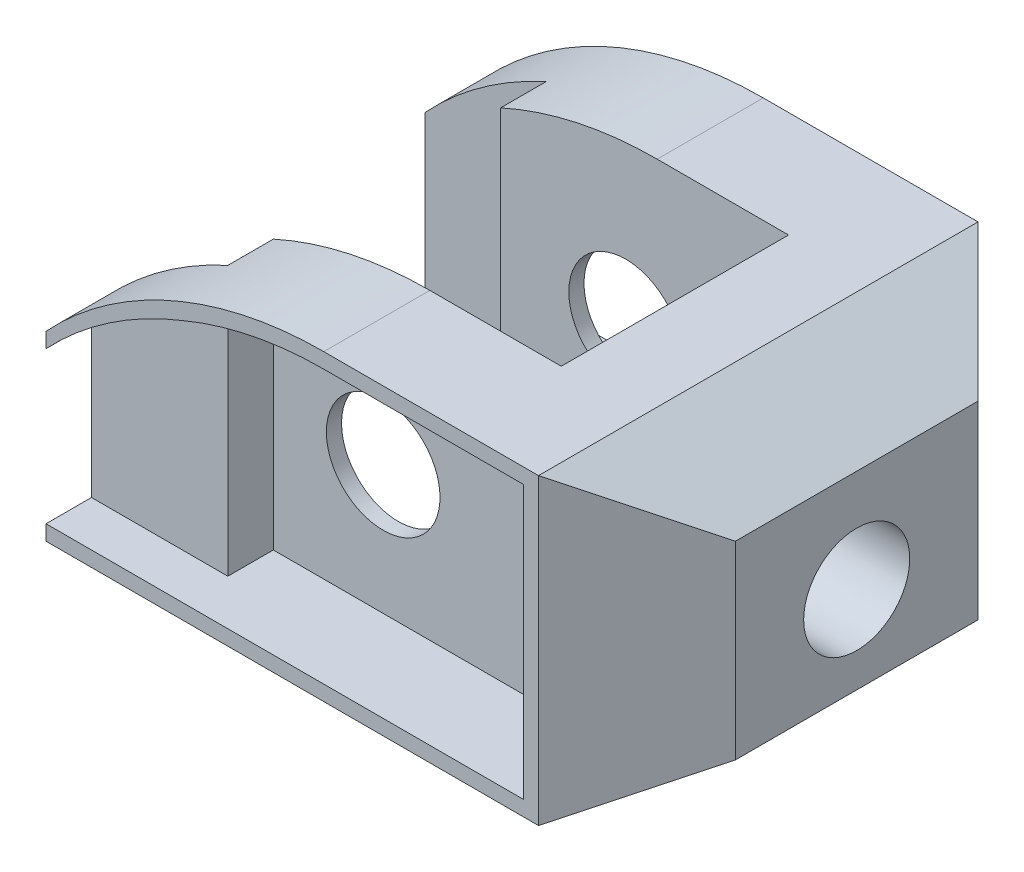
SolidWorks part; units mm, degrees
material "1060 Alloy"
ref_plane "Front Plane" through (0, 0, 0) normal (0, 0, 1) x (1, 0, 0)
ref_plane "Top Plane" through (0, 0, 0) normal (0, 1, 0) x (1, 0, 0)
ref_plane "Right Plane" through (0, 0, 0) normal (1, 0, 0) x (0, 0, -1)
sketch "Sketch1" plane through (0, 0, 0) normal (0, 0, 1) x (1, 0, 0)
  line L0 (0, 13.8138) -> (0, -28.7241) construction
  line L1 (32.5, -19) -> (-32.5, -19)
  line L2 (-32.5, -19) -> (-32.5, 5)
  line L3 (32.5, -19) -> (45.4904, -11.5)
  line L4 (45.4904, -11.5) -> (45.4904, 13.5)
  line L5 (45.4904, 13.5) -> (32.5, 21)
  line L6 (32.5, 21) -> (4.1606, 21)
  circle A0 centre (0, 0) radius 7.5
  arc A1 (-32.5, 5) -> (4.1606, 21) centre (4.1606, -29) cw
  point P8 (0, -19)
  dimension "D1" = 15
  dimension "D9" = 50
  dimension "D2" = 65
  dimension "D3" = 19
  dimension "D4" = 24
  dimension "D5" = 15
  dimension "D6" = 30
  dimension "D7" = 30
  dimension "D8" = 40
extrude "Boss-Extrude1" add sketch "Sketch1" along normal blind 58
sketch "Sketch2" plane through (0, 21, 0) normal (0, 1, 0) x (1, 0, 0)
  line L0 (45.4904, -29) -> (21.5, -29) construction
  line L1 (45.4904, -58) -> (45.4904, 0) construction
  line L2 (-32.5, -58) -> (-32.5, 0) construction
  line L3 (4.1606, -58) -> (4.1606, 0) construction
  line L4 (21.5, -44) -> (-16.5, -44)
  line L5 (21.5, -44) -> (21.5, -14)
  line L6 (21.5, -14) -> (-16.5, -14)
  line L7 (-16.5, -44) -> (-16.5, -14)
  line L8 (-16.5, -29) -> (-32.5, -29) construction
  line L9 (32.5, 0) -> (4.1606, 0) construction
  line L10 (32.5, -58) -> (32.5, 0) construction
  line L11 (32.5, -58) -> (4.1606, -58) construction
  point P6 (4.1606, -29)
  dimension "D1" = 11
  dimension "D2" = 16
  dimension "D3" = 14
  dimension "D4" = 14
extrude "Cut-Extrude1" cut sketch "Sketch2" against normal through all both and the other way through all
sketch "Sketch3" plane through (0, 21, 0) normal (0, 1, 0) x (1, 0, 0)
  line L0 (-32.5, -29) -> (45.4904, -29) construction
  line L1 (-32.5, -58) -> (-32.5, 0) construction
  line L2 (45.4904, -58) -> (45.4904, 0) construction
  line L3 (-16.5, -50) -> (-32.5, -50)
  line L4 (-16.5, -14) -> (-32.5, -14)
  line L5 (-16.5, -14) -> (-16.5, -8)
  line L6 (-16.5, -8) -> (-32.5, -8)
  line L7 (-32.5, -14) -> (-32.5, -8)
  line L8 (-32.5, -44) -> (-32.5, -50)
  line L9 (-16.5, -44) -> (-32.5, -44)
  line L10 (-16.5, -44) -> (-16.5, -50)
  dimension "D1" = 6
extrude "Cut-Extrude4" cut sketch "Sketch3" against normal through all both and the other way through all
sketch "Sketch4" plane through (45.4904, 0, 0) normal (1, 0, 0) x (0, 0, -1)
  line L0 (-58, -19) -> (0, -19) construction
  line L1 (-58, -11.5) -> (-58, 13.5) construction
  circle A0 centre (-29, 0) radius 7
  dimension "D1" = 14
  dimension "D2" = 19
  dimension "D3" = 29
extrude "Cut-Extrude5" cut sketch "Sketch4" against normal through all both and the other way through all
sketch "Sketch6" plane through (0, 21, 0) normal (0, 1, 0) x (1, 0, 0)
  line L0 (32.5, 0) -> (45.4904, -12.9904)
  line L1 (45.4904, -58) -> (45.4904, 0) construction
  line L2 (45.4904, -12.9904) -> (45.4904, 0)
  line L3 (45.4904, 0) -> (32.5, 0)
  line L4 (45.4904, -29) -> (32.5, -29) construction
  line L5 (32.5, -58) -> (32.5, 0) construction
  line L6 (45.4904, -45.0096) -> (45.4904, -58)
  line L7 (32.5, -58) -> (45.4904, -45.0096)
  line L8 (45.4904, -58) -> (32.5, -58)
  dimension "D1" = 45
extrude "Cut-Extrude6" cut sketch "Sketch6" against normal through all both and the other way through all
sketch "Sketch9" plane through (0, 0, 58) normal (0, 0, 1) x (1, 0, 0)
  line L6 (-32.5, -19) -> (32.5, -19)
  line L7 (32.5, -19) -> (32.5, 21)
  line L8 (32.5, 21) -> (4.1606, 21)
  line L9 (-32.5, 5) -> (-32.5, -19)
  line L10 (-32.5, -19) -> (32.5, -19)
  line L11 (32.5, -19) -> (32.5, 21)
  line L12 (-14.5, 15.2242) -> (-14.5, -17)
  line L13 (32.5, 21) -> (4.1606, 21)
  line L14 (-32.5, 5) -> (-32.5, -19)
  line L16 (30.5, -17) -> (30.5, 19)
  line L17 (-30.5, -17) -> (30.5, -17)
  line L18 (-30.5, 4.2061) -> (-30.5, -17)
  line L19 (30.5, 19) -> (4.1606, 19)
  line L20 (30.5, -17) -> (30.5, 19)
  line L21 (-14.5, -17) -> (30.5, -17)
  line L23 (30.5, 19) -> (4.1606, 19)
  arc A1 (4.1606, 21) -> (-32.5, 5) centre (4.1606, -29) ccw
  arc A2 (4.1606, 21) -> (-32.5, 5) centre (4.1606, -29) ccw
  arc A5 (4.1606, 19) -> (-30.5, 4.2061) centre (4.1606, -29) ccw
  arc A6 (4.1606, 19) -> (-14.5, 15.2242) centre (4.1606, -29) ccw
  point P2 (0, 0)
  point P11 (0, 0)
  circle M13 centre (0, 0) radius 7.5
  dimension "D2" = 18
  dimension "D3" = 0
  dimension "D1" = 2
extrude "Cut-Extrude10" cut sketch "Sketch9" against normal blind 12 contours L23 A6 L12 L21 L20 M13
sketch "Sketch10" plane through (0, 0, 58) normal (0, 0, 1) x (1, 0, 0)
  line L0 (-14.5, 15.2242) -> (-14.5, -17)
  line L1 (-14.5, -17) -> (-32.5, -17)
  line L2 (-32.5, 5) -> (-32.5, -19) construction
  line L3 (-32.5, -17) -> (-32.5, 3)
  arc A0 (-32.5, 3) -> (-14.5, 15.2242) centre (3.7054, -30.9475) cw
  arc A1 (4.1606, 21) -> (-32.5, 5) centre (4.1606, -29) ccw construction
  dimension "D2" = 2
  dimension "D1" = 2
extrude "Cut-Extrude12" cut sketch "Sketch10" against normal blind 6
sketch "Sketch14" plane through (0, 0, 0) normal (0, 0, -1) x (-1, 0, 0)
  line L0 (32.5, 5) -> (32.5, -19) construction
  line L11 (14.5, -17) -> (14.5, 15.2242)
  line L15 (30.5, -17) -> (30.5, 4.2061)
  line L16 (-30.5, -17) -> (30.5, -17)
  line L17 (-30.5, 19) -> (-30.5, -17)
  line L18 (-4.1606, 19) -> (-30.5, 19)
  line L20 (-30.5, -17) -> (14.5, -17)
  line L21 (-30.5, 19) -> (-30.5, -17)
  line L22 (-4.1606, 19) -> (-30.5, 19)
  arc A5 (30.5, 4.2061) -> (-4.1606, 19) centre (-4.1606, -29) ccw
  arc A6 (14.5, 15.2242) -> (-4.1606, 19) centre (-4.1606, -29) ccw
  point P2 (0, 0)
  point P3 (0, 0)
  point P4 (32.5, -17)
  point P6 (32.5, 1.9394)
  point P10 (0, 0)
  point P11 (0, 0)
  point P12 (0, 0)
  point P13 (0, 0)
  dimension "D2" = 18
  dimension "D1" = 2
extrude "Cut-Extrude13" cut sketch "Sketch14" against normal blind 12
sketch "Sketch15" plane through (0, 0, 0) normal (0, 0, -1) x (-1, 0, 0)
  line L0 (14.5, 15.2242) -> (14.5, -17)
  line L1 (14.5, -17) -> (32.5, -17)
  line L2 (32.5, -17) -> (32.5, 1.9729)
  line L3 (32.5, 5) -> (32.5, -19) construction
  arc A0 (32.5, 1.9729) -> (14.5, 15.2242) centre (-5.3585, -30.6015) ccw
  arc A1 (32.5, 5) -> (-4.1606, 21) centre (-4.1606, -29) ccw construction
  dimension "D1" = 2
extrude "Cut-Extrude14" cut sketch "Sketch15" against normal blind 6
equation "\"A\"= 58mm"
equation "\"B\"= 40mm"
equation "\"C\"= 65mm"
equation "\"D2@Sketch1\"=\"C\""
equation "\"D8@Sketch1\"=\"B\""
equation "\"D3@Sketch4\"=\"A\"/2"
